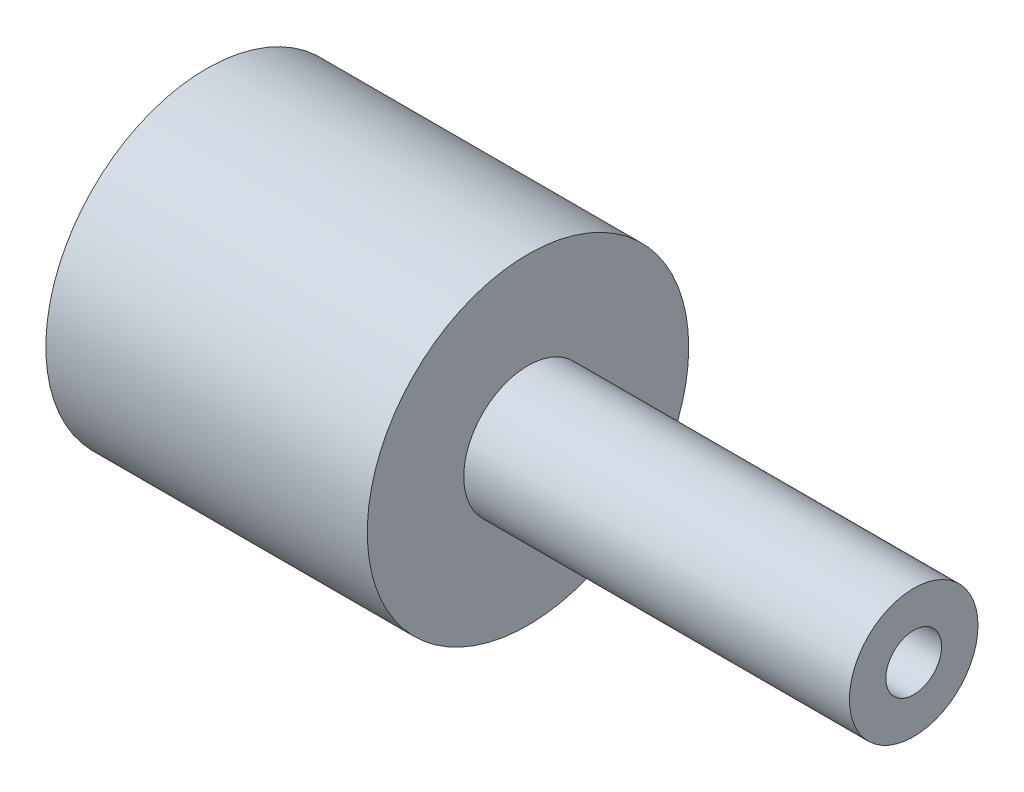
SolidWorks part; units mm, degrees
material "ナイロン"
ref_plane "正面" through (0, 0, 0) normal (0, 0, 1) x (1, 0, 0)
ref_plane "平面" through (0, 0, 0) normal (0, 1, 0) x (1, 0, 0)
ref_plane "右側面" through (0, 0, 0) normal (1, 0, 0) x (0, 0, -1)
sketch "ｽｹｯﾁ1" plane through (0, 0, 0) normal (1, 0, 0) x (0, 0, -1)
  circle A0 centre (0, 0) radius 3
  dimension "D1" = 6
extrude "ﾎﾞｽ - 押し出し1" add sketch "ｽｹｯﾁ1" along normal blind 33
sketch "ｽｹｯﾁ2" plane through (33, 0, 0) normal (1, 0, 0) x (0, 0, -1)
  circle A0 centre (0, 0) radius 1.3
  dimension "D1" = 2.6
extrude "ｶｯﾄ - 押し出し1" cut sketch "ｽｹｯﾁ2" against normal blind 5
sketch "ｽｹｯﾁ3" plane through (0, 0, 0) normal (-1, 0, 0) x (0, 0, 1)
  circle A0 centre (0, 0) radius 1.3
  dimension "D1" = 2.6
extrude "ｶｯﾄ - 押し出し2" cut sketch "ｽｹｯﾁ3" against normal blind 5
sketch "ｽｹｯﾁ4" plane through (0, 0, 0) normal (1, 0, 0) x (0, 0, -1)
  circle A0 centre (0, 0) radius 7.5
  circle A1 centre (0, 0) radius 3
  dimension "D1" = 15
  dimension "D2" = 6
extrude "ﾎﾞｽ - 押し出し2" add sketch "ｽｹｯﾁ4" along normal blind 15
